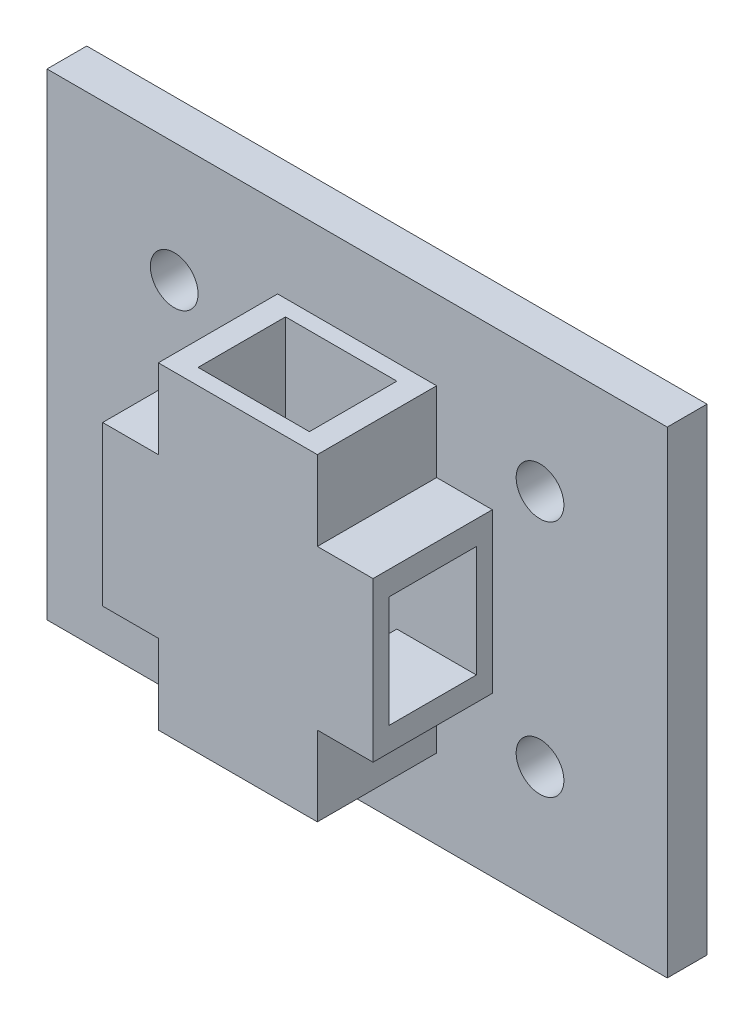
SolidWorks part; units mm, degrees
ref_plane "Front Plane" through (0, 0, 0) normal (0, 0, 1) x (1, 0, 0)
ref_plane "Top Plane" through (0, 0, 0) normal (0, 1, 0) x (1, 0, 0)
ref_plane "Right Plane" through (0, 0, 0) normal (1, 0, 0) x (0, 0, -1)
sketch "Sketch1" plane through (0, 0, 0) normal (0, 0, 1) x (1, 0, 0)
  line L1 (-39.2125, 39.1063) -> (38.7875, 39.1063)
  line L2 (-39.2125, 39.1063) -> (-39.2125, -20.8937)
  line L3 (-39.2125, -20.8937) -> (38.7875, -20.8937)
  line L4 (38.7875, 39.1063) -> (38.7875, -20.8937)
  dimension "D1" = 78
  dimension "D2" = 60
extrude "Boss-Extrude1" add sketch "Sketch1" along normal blind 5
sketch "Sketch2" plane through (0, 0, 5) normal (0, 0, 1) x (1, 0, 0)
  line L0 (38.7875, 39.1063) -> (-39.2125, 39.1063) construction
  line L1 (-17.2125, 29.1063) -> (16.7875, 29.1063)
  line L2 (-17.2125, 29.1063) -> (-17.2125, -10.8937)
  line L3 (-17.2125, -10.8937) -> (16.7875, -10.8937)
  line L4 (16.7875, 29.1063) -> (16.7875, -10.8937)
  line L5 (-39.2125, 39.1063) -> (-39.2125, -20.8937) construction
  dimension "D1" = 34
  dimension "D2" = 40
  dimension "D3" = 10
  dimension "D4" = 22
extrude "Boss-Extrude2" add sketch "Sketch2" along normal blind 15
sketch "Sketch4" plane through (0, 0, 20) normal (0, 0, 1) x (1, 0, 0)
  line L0 (-10.2125, 29.1063) -> (-10.2125, 19.1063)
  line L1 (16.7875, 29.1063) -> (-17.2125, 29.1063) construction
  line L2 (-17.2125, -10.8937) -> (16.7875, -10.8937) construction
  line L3 (9.7875, 29.1063) -> (9.7875, 19.1063)
  line L4 (16.7875, 29.1063) -> (-17.2125, 29.1063) construction
  line L5 (-17.2125, -10.8937) -> (16.7875, -10.8937) construction
  line L6 (-17.2125, 19.1063) -> (-10.2125, 19.1063)
  line L7 (-17.2125, 29.1063) -> (-17.2125, -10.8937) construction
  line L8 (16.7875, -10.8937) -> (16.7875, 29.1063) construction
  line L9 (-17.2125, -0.8937) -> (-10.2125, -0.8937)
  line L10 (-17.2125, 29.1063) -> (-17.2125, -10.8937) construction
  line L11 (16.7875, -10.8937) -> (16.7875, 29.1063) construction
  line L12 (9.7875, 19.1063) -> (16.7875, 19.1063)
  line L13 (9.7875, -0.8937) -> (9.7875, -10.8937)
  line L14 (-10.2125, -0.8937) -> (-10.2125, -10.8937)
  line L15 (9.7875, -0.8937) -> (16.7875, -0.8937)
  line L17 (-10.2125, 19.1063) -> (-17.2125, 19.1063)
  line L18 (-10.2125, 19.1063) -> (-10.2125, 29.1063)
  line L19 (-10.2125, 29.1063) -> (-17.2125, 29.1063)
  line L20 (-17.2125, 19.1063) -> (-17.2125, 29.1063)
  line L21 (9.7875, 19.1063) -> (16.7875, 19.1063)
  line L22 (9.7875, 19.1063) -> (9.7875, 29.1063)
  line L23 (9.7875, 29.1063) -> (16.7875, 29.1063)
  line L24 (16.7875, 19.1063) -> (16.7875, 29.1063)
  line L25 (9.7875, -0.8937) -> (16.7875, -0.8937)
  line L26 (9.7875, -0.8937) -> (9.7875, -10.8937)
  line L27 (9.7875, -10.8937) -> (16.7875, -10.8937)
  line L28 (16.7875, -0.8937) -> (16.7875, -10.8937)
  line L29 (-10.2125, -0.8937) -> (-17.2125, -0.8937)
  line L30 (-10.2125, -0.8937) -> (-10.2125, -10.8937)
  line L31 (-10.2125, -10.8937) -> (-17.2125, -10.8937)
  line L32 (-17.2125, -0.8937) -> (-17.2125, -10.8937)
  line M5 (-17.2125, 29.1063) -> (-17.2125, -10.8937)
  line M6 (-17.2125, -10.8937) -> (16.7875, -10.8937)
  line M7 (16.7875, -10.8937) -> (16.7875, 29.1063)
  line M8 (16.7875, 29.1063) -> (-17.2125, 29.1063)
  dimension "D1" = 20
  dimension "D2" = 20
  dimension "D3" = 7
  dimension "D4" = 10
extrude "Cut-Extrude1" cut sketch "Sketch4" against normal blind 15 contours L6 L0 M5 M8 | L3 L12 M7 M8 | L15 L13 M6 M7 | L14 L9 M5 M6
sketch "Sketch5" plane through (0, -10.8937, 0) normal (0, -1, 0) x (1, 0, 0)
  line L5 (6.7875, 7) -> (-7.2125, 7)
  line L6 (6.7875, 7) -> (6.7875, 18)
  line L7 (6.7875, 18) -> (-7.2125, 18)
  line L8 (-7.2125, 7) -> (-7.2125, 18)
  point P10 (6.7875, 12.5)
  dimension "D1" = 14
  dimension "D3" = 11
extrude "Cut-Extrude2" cut sketch "Sketch5" against normal through all
sketch "Sketch6" plane through (16.7875, 0, 0) normal (1, 0, 0) x (0, 0, -1)
  line L5 (-7, 2.1063) -> (-18, 2.1063)
  line L6 (-7, 2.1063) -> (-7, 16.1063)
  line L7 (-7, 16.1063) -> (-18, 16.1063)
  line L8 (-18, 2.1063) -> (-18, 16.1063)
  dimension "D1" = 14
  dimension "D3" = 11
extrude "Cut-Extrude3" cut sketch "Sketch6" against normal through all
sketch "Sketch7" plane through (0, 0, 5) normal (0, 0, 1) x (1, 0, 0)
  line L0 (-39.2125, 39.1063) -> (-39.2125, -20.8937) construction
  line L1 (-39.2125, -20.8937) -> (38.7875, -20.8937) construction
  line L2 (38.7875, -20.8937) -> (38.7875, 39.1063) construction
  circle A0 centre (-23.2125, 24.1063) radius 3
  circle A1 centre (22.7875, 24.1063) radius 3
  circle A2 centre (22.7875, -5.8937) radius 3
  circle A3 centre (-23.2125, -5.8937) radius 3
  point P0 (-23.2125, 24.1063)
  point P1 (22.7875, 24.1063)
  point P2 (22.7875, -5.8937)
  point P3 (-23.2125, -5.8937)
  dimension "D6" = 6
  dimension "D7" = 6
  dimension "D8" = 6
  dimension "D9" = 6
  dimension "D1" = 46
  dimension "D2" = 46
  dimension "D3" = 30
  dimension "D4" = 16
  dimension "D5" = 15
  dimension "D10" = 30
  dimension "D11" = 16
extrude "Cut-Extrude4" cut sketch "Sketch7" against normal through all
